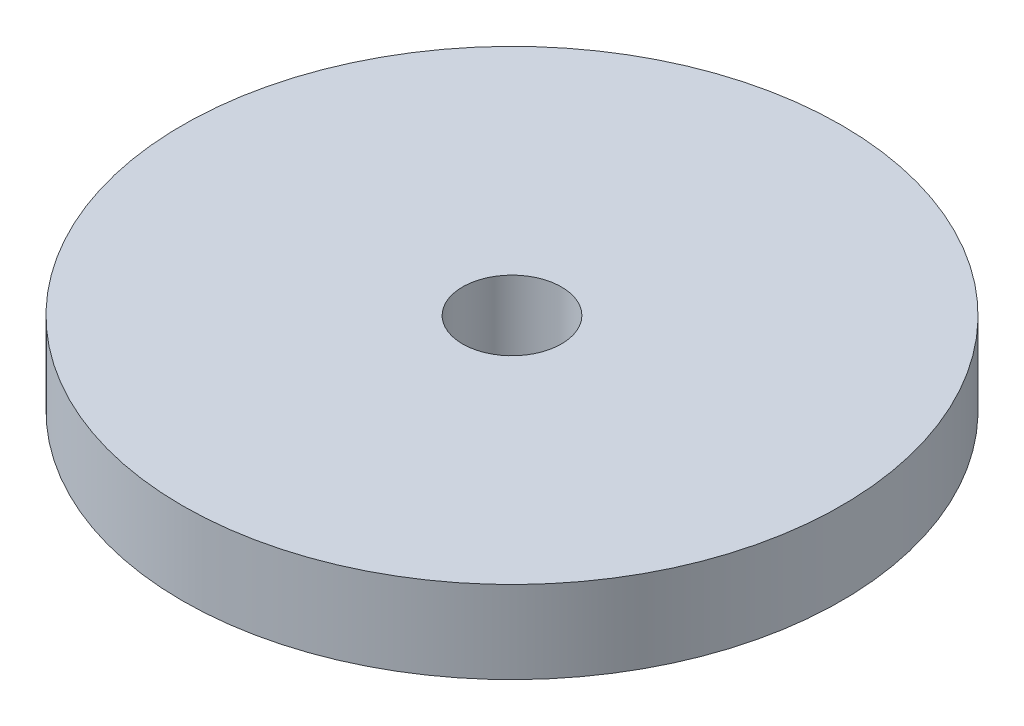
SolidWorks part; units mm, degrees
ref_plane "Front Plane" through (0, 0, 0) normal (0, 0, 1) x (1, 0, 0)
ref_plane "Top Plane" through (0, 0, 0) normal (0, 1, 0) x (1, 0, 0)
ref_plane "Right Plane" through (0, 0, 0) normal (1, 0, 0) x (0, 0, -1)
sketch "Sketch2" plane through (0, 0, 0) normal (0, 1, 0) x (1, 0, 0)
  circle A0 centre (0, 0) radius 10
  circle A1 centre (0, 0) radius 1.5
extrude "Boss-Extrude1" add sketch "Sketch2" along normal blind 2.5
